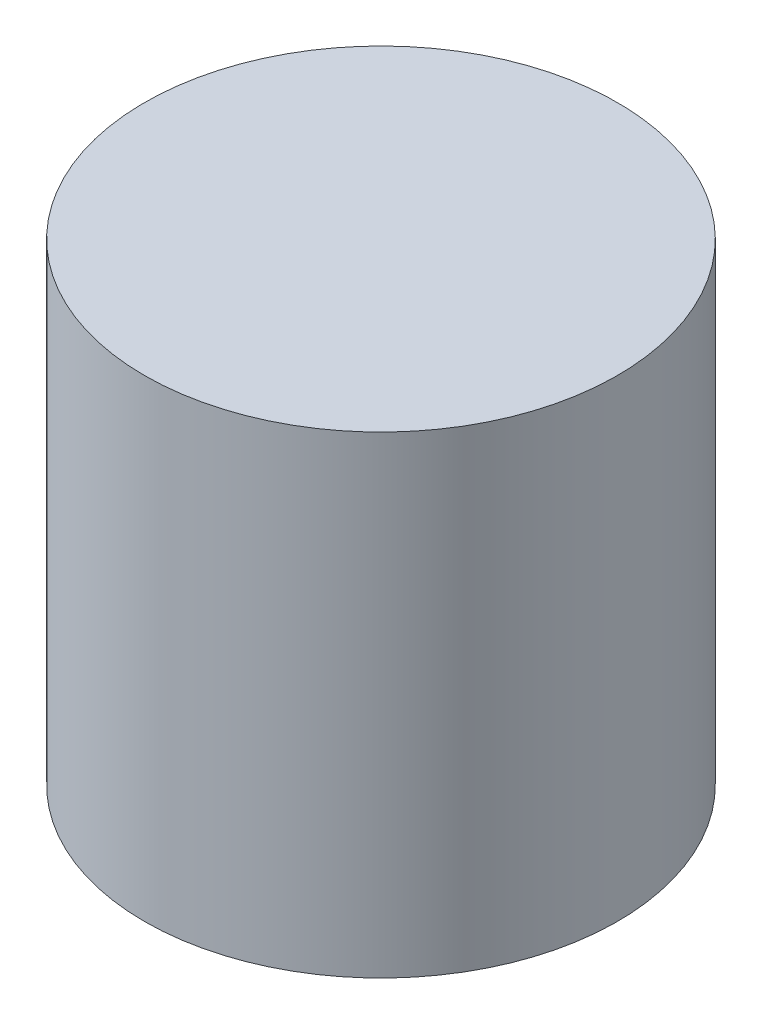
SolidWorks part; units mm, degrees
ref_plane "Front Plane" through (0, 0, 0) normal (0, 0, 1) x (1, 0, 0)
ref_plane "Top Plane" through (0, 0, 0) normal (0, 1, 0) x (1, 0, 0)
ref_plane "Right Plane" through (0, 0, 0) normal (1, 0, 0) x (0, 0, -1)
sketch "Sketch1" plane through (0, 0, 0) normal (0, 1, 0) x (1, 0, 0)
  circle A0 centre (0, 0) radius 1.27
extrude "Boss-Extrude1" add sketch "Sketch1" along normal blind 2.54
